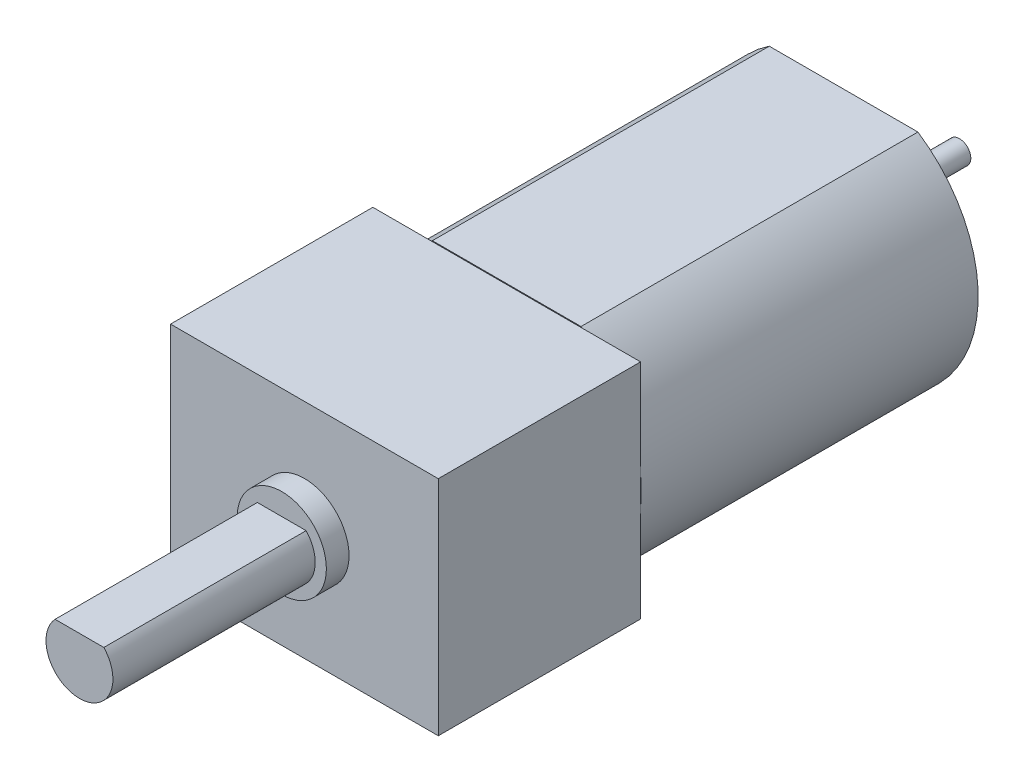
SolidWorks part; units mm, degrees
material "AISI 4340 Steel, normalized"
ref_plane "Front Plane" through (0, 0, 0) normal (0, 0, 1) x (1, 0, 0)
ref_plane "Top Plane" through (0, 0, 0) normal (0, 1, 0) x (1, 0, 0)
ref_plane "Right Plane" through (0, 0, 0) normal (1, 0, 0) x (0, 0, -1)
sketch "Sketch1" plane through (0, 0, 0) normal (0, 0, 1) x (1, 0, 0)
  line L1 (5.5869, -3.9629) -> (17.5884, -3.9629)
  line L2 (5.5869, -3.9629) -> (5.5869, -13.9451)
  line L3 (5.5869, -13.9451) -> (17.5884, -13.9451)
  line L4 (17.5884, -3.9629) -> (17.5884, -13.9451)
  line L8 (11.5876, -3.9629) -> (11.5876, -13.9451) construction
  line L9 (5.5869, -8.954) -> (17.5884, -8.954) construction
  dimension "D1" = 9.9822
  dimension "D2" = 12.0015
extrude "Boss-Extrude4" add sketch "Sketch1" along normal blind 9.0678
sketch "Sketch3" plane through (0, 0, 0) normal (0, 0, -1) x (-1, 0, 0)
  line L0 (-11.5876, -3.9629) -> (-11.5876, -13.9451) construction
  line L1 (-17.5884, -3.9629) -> (-5.5869, -3.9629) construction
  line L2 (-5.5869, -13.9451) -> (-17.5884, -13.9451) construction
  line L3 (-17.5884, -8.954) -> (-5.5869, -8.954) construction
  line L4 (-17.5884, -13.9451) -> (-17.5884, -3.9629) construction
  line L5 (-5.5869, -3.9629) -> (-5.5869, -13.9451) construction
  line L6 (-14.919, -3.9248) -> (-8.2562, -3.9248)
  line L7 (-14.919, -13.9832) -> (-8.2562, -13.9832)
  arc A0 (-14.919, -3.9248) -> (-14.919, -13.9832) centre (-11.5876, -8.954) ccw
  arc A1 (-8.2562, -13.9832) -> (-8.2562, -3.9248) centre (-11.5876, -8.954) ccw
  dimension "D1" = 12.065
  dimension "D2" = 5.0292
extrude "Boss-Extrude5" add sketch "Sketch3" along normal blind 15.1003
sketch "Sketch4" plane through (0, 0, 9.0678) normal (0, 0, 1) x (1, 0, 0)
  line L0 (11.5876, -3.9629) -> (11.5876, -13.9451) construction
  line L1 (17.5884, -3.9629) -> (5.5869, -3.9629) construction
  line L2 (5.5869, -13.9451) -> (17.5884, -13.9451) construction
  line L3 (5.5869, -8.954) -> (17.5884, -8.954) construction
  line L4 (5.5869, -3.9629) -> (5.5869, -13.9451) construction
  line L5 (17.5884, -13.9451) -> (17.5884, -3.9629) construction
  circle A0 centre (11.5876, -8.954) radius 2.0003
  dimension "D1" = 4.0005
extrude "Boss-Extrude9" add sketch "Sketch4" along normal blind 1.016
sketch "Sketch5" plane through (0, 0, 10.0838) normal (0, 0, 1) x (1, 0, 0)
  line L0 (11.5876, -6.9537) -> (11.5876, -10.9542) construction
  line L1 (9.5874, -8.954) -> (13.5879, -8.954) construction
  line L2 (11.5876, -7.454) -> (11.5876, -10.454) construction
  line L3 (10.0876, -8.954) -> (13.0876, -8.954) construction
  line L4 (10.4946, -7.9267) -> (12.6806, -7.9267)
  circle A0 centre (11.5876, -8.954) radius 2.0003 construction
  arc A1 (10.4946, -7.9267) -> (12.6806, -7.9267) centre (11.5876, -8.954) ccw
  dimension "D1" = 3
  dimension "D2" = 2.5273
extrude "Boss-Extrude10" add sketch "Sketch5" along normal blind 9.0678
sketch "Sketch6" plane through (0, 0, -15.1003) normal (0, 0, -1) x (-1, 0, 0)
  line L0 (-11.5876, -3.9248) -> (-11.5876, -13.9832) construction
  line L1 (-8.2562, -3.9248) -> (-14.919, -3.9248) construction
  line L2 (-14.919, -13.9832) -> (-8.2562, -13.9832) construction
  line L3 (-17.6201, -8.954) -> (-5.5551, -8.954) construction
  arc A0 (-14.919, -3.9248) -> (-14.919, -13.9832) centre (-11.5876, -8.954) ccw construction
  arc A1 (-8.2562, -13.9832) -> (-8.2562, -3.9248) centre (-11.5876, -8.954) ccw construction
  circle A2 centre (-11.5876, -8.954) radius 2.5146
  dimension "D1" = 5.0292
extrude "Boss-Extrude11" add sketch "Sketch6" along normal blind 0.889
sketch "Sketch7" plane through (0, 0, -15.9893) normal (0, 0, -1) x (-1, 0, 0)
  line L0 (-11.5876, -6.4394) -> (-11.5876, -11.4686) construction
  line L1 (-14.1022, -8.954) -> (-9.073, -8.954) construction
  circle A0 centre (-11.5876, -8.954) radius 2.5146 construction
  circle A1 centre (-11.5876, -8.954) radius 0.508
  dimension "D1" = 1.016
extrude "Boss-Extrude12" add sketch "Sketch7" along normal blind 4.3053
